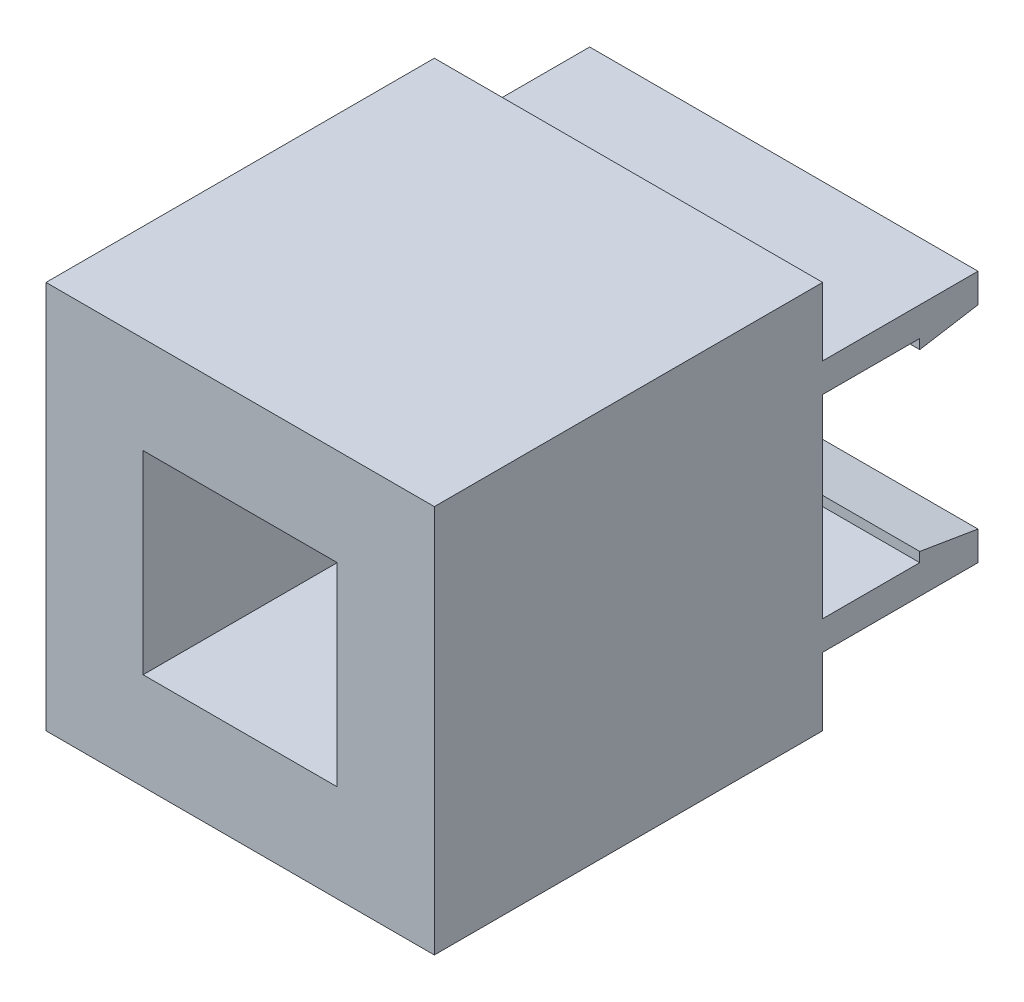
SolidWorks part; units mm, degrees
ref_plane "前视基准面" through (0, 0, 0) normal (0, 0, 1) x (1, 0, 0)
ref_plane "上视基准面" through (0, 0, 0) normal (0, 1, 0) x (1, 0, 0)
ref_plane "右视基准面" through (0, 0, 0) normal (1, 0, 0) x (0, 0, -1)
sketch "草图1" plane through (0, 0, 0) normal (0, 0, 1) x (1, 0, 0)
  line L0 (-5, 15) -> (15, 15)
  line L1 (0, 0) -> (10, 0)
  line L2 (0, 0) -> (0, 10)
  line L3 (0, 10) -> (10, 10)
  line L4 (10, 0) -> (10, 10)
  line L5 (15, -5) -> (15, 15)
  line L6 (-5, -5) -> (15, -5)
  line L7 (-5, -5) -> (-5, 15)
  dimension "D1" = 10
  dimension "D2" = 10
  dimension "D3" = 5
extrude "凸台-拉伸1" add sketch "草图1" along normal blind 20
sketch "草图2" plane through (0, 0, 0) normal (0, 0, -1) x (-1, 0, 0)
  line L0 (5, 15) -> (5, -5) construction
  line L1 (5, 10) -> (-15, 10)
  line L2 (5, 10) -> (5, 13)
  line L3 (5, 13) -> (-15, 13)
  line L4 (-15, 10) -> (-15, 13)
  line L5 (-15, -5) -> (-15, 15) construction
  line L6 (0, 0) -> (-10, 0) construction
  line L7 (5, 0) -> (-15, 0)
  line L8 (5, 0) -> (5, -3)
  line L9 (5, -3) -> (-15, -3)
  line L10 (-15, 0) -> (-15, -3)
  line L11 (-10, 10) -> (0, 10) construction
  dimension "D1" = 3
  dimension "D2" = 3
extrude "凸台-拉伸2" add sketch "草图2" along normal blind 5
sketch "草图3" plane through (-5, 0, 0) normal (-1, 0, 0) x (0, 0, 1)
  line L0 (-5, 10) -> (-5, 9.5)
  line L1 (-5, 0) -> (-5, 0.5)
  line L2 (-5, -3) -> (-8, -3)
  line L3 (-8, -3) -> (-8, 0)
  line L4 (-8, 0) -> (-5, 0.5)
  line L5 (-5, 13) -> (-8, 13)
  line L6 (-8, 13) -> (-8, 10)
  line L7 (-8, 10) -> (-5, 9.5)
  line L8 (-5, 10) -> (-5, 13)
  line L9 (-5, -3) -> (-5, 0)
  dimension "D1" = 0.5
  dimension "D2" = 0.5
  dimension "D3" = 3
  dimension "D4" = 3
extrude "凸台-拉伸3" add sketch "草图3" against normal blind 20
sketch "草图4" plane through (-5, 0, 0) normal (-1, 0, 0) x (0, 0, 1)
  line L1 (-8, 13) -> (0, 13)
  line L2 (-8, 13) -> (-8, 11.5)
  line L3 (-8, 11.5) -> (0, 11.5)
  line L4 (0, 13) -> (0, 11.5)
  line L5 (-8, -3) -> (0, -3)
  line L6 (-8, -3) -> (-8, -1.5)
  line L7 (-8, -1.5) -> (0, -1.5)
  line L8 (0, -3) -> (0, -1.5)
  dimension "D1" = 1.5
  dimension "D2" = 1.5
extrude "切除-拉伸1" cut sketch "草图4" against normal blind 20
